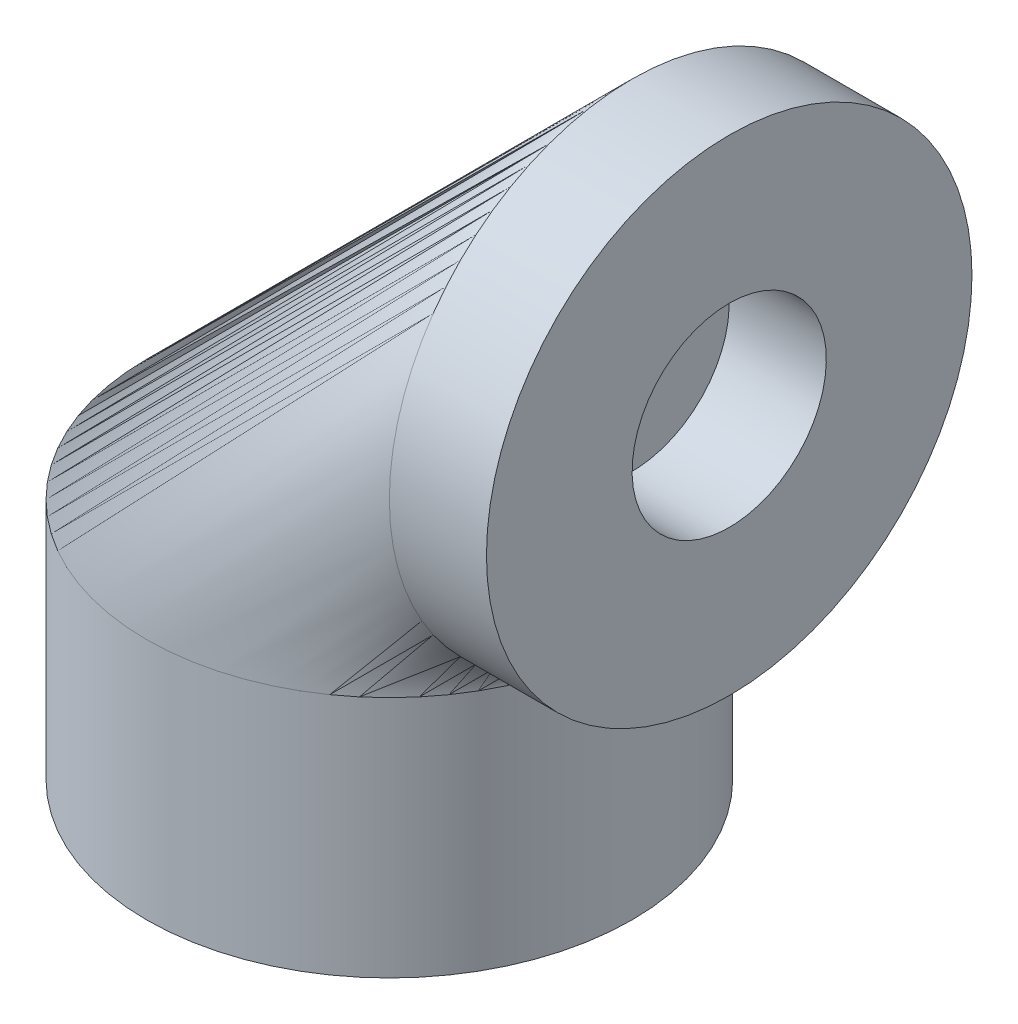
SolidWorks part; units mm, degrees
ref_plane "Front Plane" through (0, 0, 0) normal (0, 0, 1) x (1, 0, 0)
ref_plane "Top Plane" through (0, 0, 0) normal (0, 1, 0) x (1, 0, 0)
ref_plane "Right Plane" through (0, 0, 0) normal (1, 0, 0) x (0, 0, -1)
sketch "Sketch1" plane through (0, 0, 0) normal (0, 1, 0) x (1, 0, 0)
  circle A0 centre (0, 0) radius 50
extrude "Boss-Extrude1" add sketch "Sketch1" along normal blind 50
sketch "Sketch2" plane through (0, 50, 0) normal (0, 1, 0) x (1, 0, 0)
  circle A0 centre (0, 0) radius 50
sketch "Sketch3" plane through (0, 0, 0) normal (0, 0, 1) x (1, 0, 0)
  arc A0 (50, 100) -> (0, 50) centre (50, 50) ccw
sweep "Sweep1" add profiles "Sketch2" path "Sketch3"
sketch "Sketch5" plane through (50, 0, 0) normal (1, 0, 0) x (0, 0, -1)
  line L0 (0, 100) -> (0, 50) construction
  circle A0 centre (0, 100) radius 50
extrude "Boss-Extrude2" add sketch "Sketch5" along normal blind 20
sketch "Sketch6" plane through (70, 0, 0) normal (1, 0, 0) x (0, 0, -1)
  circle A0 centre (0, 100) radius 20
extrude "Cut-Extrude1" cut sketch "Sketch6" against normal blind 20
sketch "Sketch7" plane through (0, 0, 0) normal (0, -1, 0) x (1, 0, 0)
  circle A0 centre (0, 0) radius 20
extrude "Boss-Extrude3" add sketch "Sketch7" along normal blind 20
